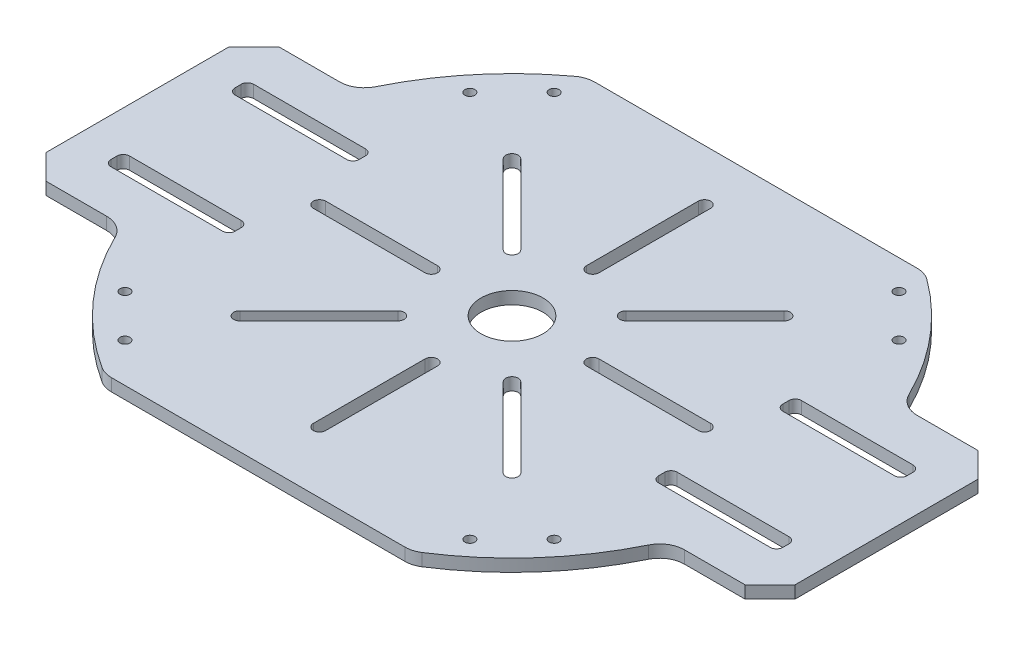
SolidWorks part; units mm, degrees
ref_plane "Front Plane" through (0, 0, 0) normal (0, 0, 1) x (1, 0, 0)
ref_plane "Top Plane" through (0, 0, 0) normal (0, 1, 0) x (1, 0, 0)
ref_plane "Right Plane" through (0, 0, 0) normal (1, 0, 0) x (0, 0, -1)
sketch "Sketch1" plane through (0, 0, 0) normal (0, 1, 0) x (1, 0, 0)
  line L0 (0, -1000) -> (0, 49000) construction
  line L1 (-32.9682, 49.8761) -> (32.9682, 49.8761)
  line L2 (-76.5969, 18.7325) -> (-76.5969, -18.7289)
  line L3 (-30, -51.9158) -> (30, -51.9158)
  line L4 (76.5969, 18.7289) -> (76.5969, -18.7289)
  line L6 (35.4178, 36.4243) -> (37.7064, 37.571) construction
  line L7 (-76.5969, 0) -> (76.5969, 0) construction
  line L8 (-71.5169, 23.8125) -> (-59.0952, 23.8125)
  line L9 (-71.5169, -23.8089) -> (-59.0969, -23.8089)
  line L10 (-30, 64.7529) -> (-30, -51.9158) construction
  line L11 (30, 64.7529) -> (30, -51.9158) construction
  line L12 (59.0969, -23.8089) -> (71.5169, -23.8089)
  line L13 (59.0969, 23.8089) -> (71.5169, 23.8089)
  line L14 (-76.5969, -18.7289) -> (-71.5169, -23.8089)
  line L15 (-71.5169, 23.8125) -> (-76.5969, 18.7325)
  line L16 (71.5169, 23.8089) -> (76.5969, 18.7289)
  line L17 (71.5169, -23.8089) -> (76.5969, -18.7289)
  line L18 (707.1067, -707.1067) -> (-34648.2323, 34648.2323) construction
  line L19 (-706.2853, -706.2853) -> (34610.598, 34610.5979) construction
  circle A0 centre (0, 0) radius 6.35
  arc A1 (-35.9793, 48.8875) -> (-54.5314, 26.6612) centre (0, 0) ccw
  arc A2 (35.9793, 48.8875) -> (32.9682, 49.8761) centre (32.9682, 44.7961) ccw
  arc A3 (-32.9682, 49.8761) -> (-35.9793, 48.8875) centre (-32.9682, 44.7961) ccw
  arc A4 (32.74, -51.1135) -> (54.533, -26.6579) centre (0, 0) ccw
  arc A5 (32.74, -51.1135) -> (30, -51.9158) centre (30, -46.8358) cw
  arc A6 (-32.74, -51.1135) -> (-30, -51.9158) centre (-30, -46.8358) ccw
  arc A7 (-54.533, -26.6579) -> (-32.74, -51.1135) centre (0, 0) ccw
  arc A8 (54.533, 26.6579) -> (35.9793, 48.8875) centre (0, 0) ccw
  arc A9 (-59.0969, -23.8089) -> (-54.533, -26.6579) centre (-59.0969, -28.8889) cw
  arc A10 (59.0969, -23.8089) -> (54.533, -26.6579) centre (59.0969, -28.8889) ccw
  arc A11 (54.533, 26.6579) -> (59.0969, 23.8089) centre (59.0969, 28.8889) ccw
  arc A12 (-59.0952, 23.8125) -> (-54.5314, 26.6612) centre (-59.0952, 28.8925) ccw
  circle A13 centre (43.8949, 35.2739) radius 1.016
  circle A14 centre (35.2739, 43.8949) radius 1.016
  circle A15 centre (26.6949, 26.6949) radius 0.081
  circle A16 centre (26.6949, -26.6949) radius 0.081
  circle A17 centre (43.8949, -35.2739) radius 1.016
  circle A18 centre (35.2739, -43.8949) radius 1.016
  circle A19 centre (-26.6949, -26.6949) radius 0.081
  circle A20 centre (-35.2739, -43.8949) radius 1.016
  circle A21 centre (-43.8949, -35.2739) radius 1.016
  circle A22 centre (-26.6949, 26.6949) radius 0.081
  circle A23 centre (-43.8949, 35.2739) radius 1.016
  circle A24 centre (-35.2739, 43.8949) radius 1.016
  point P0 (0, 0)
  point P8 (76.5969, -23.8089)
  point P11 (-76.5969, -23.8089)
  point P12 (-76.5969, 23.8125)
  point P34 (76.5969, 23.8089)
  point P60 (-43.8949, -35.2739)
  point P61 (43.8949, -35.2739)
  point P62 (35.2739, 43.8949)
  point P81 (0, 0)
  point P86 (-30, -49.1098)
  point P87 (0, 0)
  dimension "D3" = 12.7
  dimension "D6" = 5.08
  dimension "D1" = 5.08
  dimension "D2" = 5.08
  dimension "D7" = 4.826
  dimension "D5" = 23.8125
  dimension "D8" = 6.096
  dimension "D13" = 4
extrude "Boss-Extrude1" add sketch "Sketch1" along normal blind 2.54
sketch "Sketch3" plane through (0, 2.54, 0) normal (0, 1, 0) x (1, 0, 0)
  line L0 (0, 0) -> (46.2784, 46.2784) construction
  line L1 (10.7763, 12.5724) -> (26.9408, 28.7368)
  line L2 (16.51, -1.27) -> (39.37, -1.27)
  line L3 (16.51, 1.27) -> (39.37, 1.27)
  line L4 (12.5724, 10.7763) -> (28.7368, 26.9408)
  line L5 (10.5167, 12.1967) -> (28.9964, 27.3164) construction
  line L6 (19.7566, 19.7566) -> (12.1967, 10.5167) construction
  line L7 (42.9214, 42.9214) -> (45.5684, 40.2744) construction
  line L8 (10.7763, -12.5724) -> (26.9408, -28.7368)
  line L9 (12.5724, -10.7763) -> (28.7368, -26.9408)
  line L10 (-1.27, -16.51) -> (-1.27, -39.37)
  line L11 (1.27, -16.51) -> (1.27, -39.37)
  line L12 (-12.5724, -10.7763) -> (-28.7368, -26.9408)
  line L13 (-10.7763, -12.5724) -> (-26.9408, -28.7368)
  line L14 (-16.51, 1.27) -> (-39.37, 1.27)
  line L15 (-16.51, -1.27) -> (-39.37, -1.27)
  line L16 (-10.7763, 12.5724) -> (-26.9408, 28.7368)
  line L17 (-12.5724, 10.7763) -> (-28.7368, 26.9408)
  line L18 (1.27, 16.51) -> (1.27, 39.37)
  line L19 (-1.27, 16.51) -> (-1.27, 39.37)
  arc A0 (54.533, 26.6579) -> (35.9793, 48.8875) centre (0, 0) ccw construction
  arc A1 (28.7368, 26.9408) -> (26.9408, 28.7368) centre (27.8388, 27.8388) ccw
  arc A2 (10.7763, 12.5724) -> (12.5724, 10.7763) centre (11.6743, 11.6743) ccw
  arc A3 (39.37, -1.27) -> (39.37, 1.27) centre (39.37, 0) ccw
  arc A4 (16.51, 1.27) -> (16.51, -1.27) centre (16.51, 0) ccw
  arc A5 (26.9408, -28.7368) -> (28.7368, -26.9408) centre (27.8388, -27.8388) ccw
  arc A6 (12.5724, -10.7763) -> (10.7763, -12.5724) centre (11.6743, -11.6743) ccw
  arc A7 (-1.27, -39.37) -> (1.27, -39.37) centre (0, -39.37) ccw
  arc A8 (1.27, -16.51) -> (-1.27, -16.51) centre (0, -16.51) ccw
  arc A9 (-28.7368, -26.9408) -> (-26.9408, -28.7368) centre (-27.8388, -27.8388) ccw
  arc A10 (-10.7763, -12.5724) -> (-12.5724, -10.7763) centre (-11.6743, -11.6743) ccw
  arc A11 (-39.37, 1.27) -> (-39.37, -1.27) centre (-39.37, 0) ccw
  arc A12 (-16.51, -1.27) -> (-16.51, 1.27) centre (-16.51, 0) ccw
  arc A13 (-26.9408, 28.7368) -> (-28.7368, 26.9408) centre (-27.8388, 27.8388) ccw
  arc A14 (-12.5724, 10.7763) -> (-10.7763, 12.5724) centre (-11.6743, 11.6743) ccw
  arc A15 (1.27, 39.37) -> (-1.27, 39.37) centre (0, 39.37) ccw
  arc A16 (-1.27, 16.51) -> (1.27, 16.51) centre (0, 16.51) ccw
  point P4 (19.7566, 19.7566)
  point P64 (0, 0)
  dimension "D1" = 8
  dimension "D3" = 1.27
extrude "Cut-Extrude1" cut sketch "Sketch3" against normal blind 2.54
sketch "Sketch4" plane through (0, 2.54, 0) normal (0, 1, 0) x (1, 0, 0)
  line L0 (-1000, 0) -> (49000, 0) construction
  line L1 (76.5969, -18.7289) -> (76.5969, 18.7289) construction
  line L2 (44.5929, 14.605) -> (67.4529, 14.605)
  line L3 (43.3229, 13.335) -> (43.3229, 12.065)
  line L4 (44.5929, 10.795) -> (67.4529, 10.795)
  line L5 (68.7229, 13.335) -> (68.7229, 12.065)
  line L6 (43.3229, 14.605) -> (68.7229, 10.795) construction
  line L7 (43.3229, 10.795) -> (68.7229, 14.605) construction
  line L8 (68.7229, -13.335) -> (68.7229, -12.065)
  line L9 (44.5929, -10.795) -> (67.4529, -10.795)
  line L10 (43.3229, -13.335) -> (43.3229, -12.065)
  line L11 (44.5929, -14.605) -> (67.4529, -14.605)
  line L12 (0, 0) -> (0, -50000) construction
  line L13 (-44.5929, -14.605) -> (-67.4529, -14.605)
  line L14 (-43.3229, -13.335) -> (-43.3229, -12.065)
  line L15 (-44.5929, -10.795) -> (-67.4529, -10.795)
  line L16 (-68.7229, -13.335) -> (-68.7229, -12.065)
  line L17 (-43.3229, 10.795) -> (-68.7229, 14.605) construction
  line L18 (-43.3229, 14.605) -> (-68.7229, 10.795) construction
  line L19 (-68.7229, 13.335) -> (-68.7229, 12.065)
  line L20 (-44.5929, 10.795) -> (-67.4529, 10.795)
  line L21 (-43.3229, 13.335) -> (-43.3229, 12.065)
  line L22 (-44.5929, 14.605) -> (-67.4529, 14.605)
  arc A0 (44.5929, 10.795) -> (43.3229, 12.065) centre (44.5929, 12.065) cw
  arc A1 (43.3229, 13.335) -> (44.5929, 14.605) centre (44.5929, 13.335) cw
  arc A2 (68.7229, 12.065) -> (67.4529, 10.795) centre (67.4529, 12.065) cw
  arc A3 (68.7229, 13.335) -> (67.4529, 14.605) centre (67.4529, 13.335) ccw
  arc A4 (68.7229, -12.065) -> (67.4529, -10.795) centre (67.4529, -12.065) ccw
  arc A5 (68.7229, -13.335) -> (67.4529, -14.605) centre (67.4529, -13.335) cw
  arc A6 (44.5929, -10.795) -> (43.3229, -12.065) centre (44.5929, -12.065) ccw
  arc A7 (43.3229, -13.335) -> (44.5929, -14.605) centre (44.5929, -13.335) ccw
  arc A8 (-43.3229, -13.335) -> (-44.5929, -14.605) centre (-44.5929, -13.335) cw
  arc A9 (-44.5929, -10.795) -> (-43.3229, -12.065) centre (-44.5929, -12.065) cw
  arc A10 (-68.7229, -13.335) -> (-67.4529, -14.605) centre (-67.4529, -13.335) ccw
  arc A11 (-68.7229, -12.065) -> (-67.4529, -10.795) centre (-67.4529, -12.065) cw
  arc A12 (-68.7229, 13.335) -> (-67.4529, 14.605) centre (-67.4529, 13.335) cw
  arc A13 (-68.7229, 12.065) -> (-67.4529, 10.795) centre (-67.4529, 12.065) ccw
  arc A14 (-43.3229, 13.335) -> (-44.5929, 14.605) centre (-44.5929, 13.335) ccw
  arc A15 (-44.5929, 10.795) -> (-43.3229, 12.065) centre (-44.5929, 12.065) ccw
  point P1 (56.0229, 12.7)
  point P64 (-56.0229, 12.7)
  dimension "D5" = 1.27
  dimension "D1" = 25.4
  dimension "D2" = 3.81
  dimension "D3" = 7.874
  dimension "D4" = 10.795
extrude "Cut-Extrude2" cut sketch "Sketch4" against normal blind 2.54
